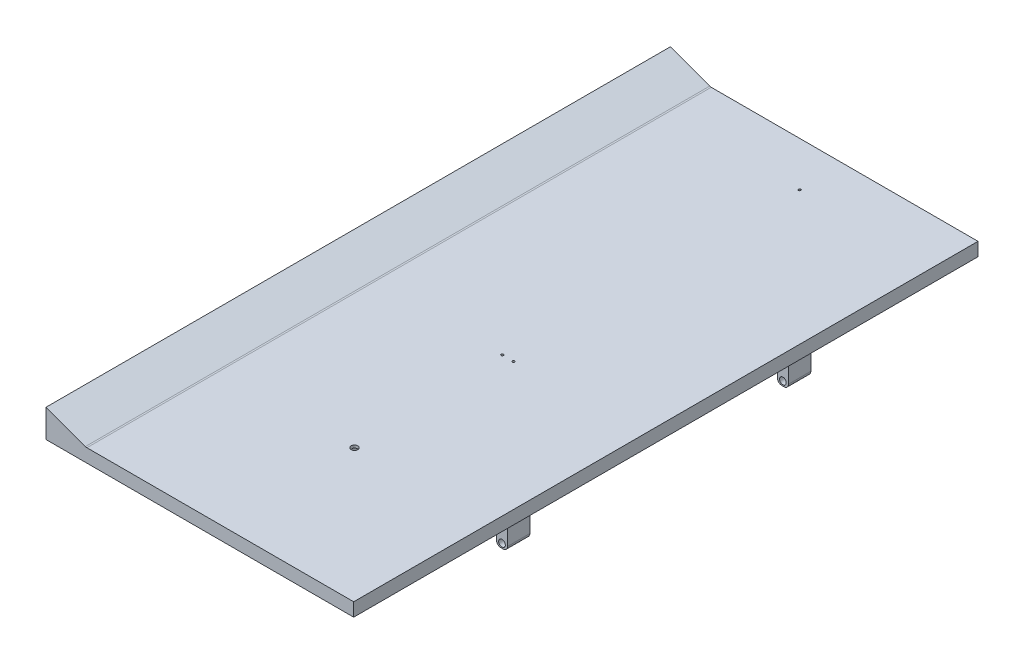
SolidWorks part; units mm, degrees
ref_plane "Front Plane" through (0, 0, 0) normal (0, 0, 1) x (1, 0, 0)
ref_plane "Top Plane" through (0, 0, 0) normal (0, 1, 0) x (1, 0, 0)
ref_plane "Right Plane" through (0, 0, 0) normal (1, 0, 0) x (0, 0, -1)
sketch "Sketch1" plane through (0, 0, 0) normal (0, 0, 1) x (1, 0, 0)
  line L0 (0, 0) -> (-598.2367, 0)
  line L1 (-601.6569, 0.6031) -> (-690, 32.7573)
  line L6 (-656.4457, -30) -> (-26.4461, -30)
  line L7 (0, -20.0005) -> (0, 0)
  line L8 (-26.4461, -30) -> (0, -30)
  line L11 (-656.4457, -30) -> (-690, -30)
  line L12 (0, -20.0005) -> (0, -30)
  line L13 (-690, -30) -> (-690, 32.7573)
  arc A2 (-598.2367, 0) -> (-601.6569, 0.6031) centre (-598.2367, 10) cw
  point P9 (-690, -30)
  point P14 (-600, 0)
  dimension "D1" = 30
  dimension "D2" = 690
  dimension "D3" = 600
  dimension "D5" = 160
extrude "Boss-Extrude1" add sketch "Sketch1" along normal blind 1040 and the other way blind 360
sketch "Sketch2" plane through (0, 0, 0) normal (0, 0, 1) x (1, 0, 0)
  line L0 (-690, 32.7573) -> (-690, -286.128) construction
  line L1 (0, -223.3332) -> (0, 223.3332) construction
  line L3 (-690, -30) -> (0, -30) construction
  line L4 (-677.5, -80) -> (-352.5, -80) construction
  line L5 (-677.5, -72.5) -> (-352.5, -72.5)
  line L6 (-677.5, -87.5) -> (-352.5, -87.5)
  line L7 (-690, -30) -> (-690, -80)
  line L8 (-680, -90) -> (-350, -90)
  line L9 (-340, -80) -> (-340, -30)
  line L10 (-690, -30) -> (0, -30) construction
  line L11 (-340, -30) -> (-690, -30)
  line L12 (-15, -30) -> (-15, -80)
  line L13 (-25, -90) -> (-30, -90)
  line L14 (-40, -80) -> (-40, -30)
  line L15 (-40, -30) -> (-15, -30)
  circle A0 centre (-27.5, -80) radius 7.5
  arc A1 (-677.5, -72.5) -> (-677.5, -87.5) centre (-677.5, -80) ccw
  arc A2 (-352.5, -87.5) -> (-352.5, -72.5) centre (-352.5, -80) ccw
  arc A3 (-690, -80) -> (-680, -90) centre (-680, -80) ccw
  arc A4 (-350, -90) -> (-340, -80) centre (-350, -80) ccw
  arc A5 (-15, -80) -> (-25, -90) centre (-25, -80) cw
  arc A6 (-30, -90) -> (-40, -80) centre (-30, -80) cw
  point P7 (0, 0)
  point P14 (-515, -80)
  point P29 (-690, -90)
  point P32 (-340, -90)
  point P40 (-15, -90)
  point P43 (-40, -90)
  dimension "D1" = 27.5
  dimension "D2" = 50
  dimension "D5" = 325
  dimension "D4" = 7.5
  dimension "D6" = 15
  dimension "D9" = 10
  dimension "D10" = 10
  dimension "D13" = 10
  dimension "D14" = 12.5
  dimension "D15" = 12.5
  dimension "D3" = 325
  dimension "D7" = 60
  dimension "D8" = 350
  dimension "D11" = 60
  dimension "D12" = 25
extrude "Boss-Extrude2" add sketch "Sketch2" along normal blind 680
sketch "Sketch4" plane through (0, 0, 0) normal (1, 0, 0) x (0, 0, -1)
  line L0 (-50, -90) -> (-50, -80)
  line L1 (-680, -90) -> (0, -90) construction
  line L2 (-680, -80) -> (0, -80) construction
  line L3 (-50, -80) -> (-630, -80)
  line L4 (-630, -80) -> (-630, -90)
  line L5 (-630, -90) -> (-50, -90)
  line L7 (-680, -80) -> (-680, -30) construction
  dimension "D1" = 580
  dimension "D2" = 50
extrude "Cut-Extrude1" cut sketch "Sketch4" against normal through all
sketch "Sketch5" plane through (-690, 0, 0) normal (-1, 0, 0) x (0, 0, 1)
  line L0 (630, -80) -> (630, -30)
  line L1 (-360, -30) -> (1040, -30) construction
  line L2 (50, -80) -> (50, -30)
  line L3 (50, -30) -> (630, -30)
  line L4 (630, -80) -> (50, -80)
extrude "Cut-Extrude2" cut sketch "Sketch5" against normal through all both and the other way through all
sketch "Sketch6" plane through (0, 0, 0) normal (0, 1, 0) x (1, 0, 0)
  line L0 (0, 360) -> (-690, 360) construction
  line L1 (-298.2367, 60) -> (-298.2367, -740) construction
  line L2 (0, -1040) -> (-598.2367, -1040) construction
  line L3 (122.7597, -740) -> (-719.2332, -740) construction
  line L4 (-598.2367, 360) -> (-598.2367, -1040) construction
  circle A0 centre (-298.2367, -740) radius 7.5
  point P11 (-298.2367, -740)
  dimension "D2" = 15
  dimension "D1" = 300
  dimension "D3" = 300
extrude "Cut-Extrude3" cut sketch "Sketch6" along normal through all both and the other way through all
sketch "Sketch8" plane through (0, -30, 0) normal (0, -1, 0) x (1, 0, 0)
  line L1 (-310.7367, 756) -> (-285.7367, 756)
  line L2 (-310.7367, 756) -> (-310.7367, 724)
  line L3 (-310.7367, 724) -> (-285.7367, 724)
  line L4 (-285.7367, 756) -> (-285.7367, 724)
  line L5 (-310.7367, 756) -> (-285.7367, 724) construction
  line L6 (-310.7367, 724) -> (-285.7367, 756) construction
  point P0 (-298.2367, 740)
  dimension "D1" = 32
  dimension "D2" = 25
extrude "Boss-Extrude4" add sketch "Sketch8" along normal blind 37.5
sketch "Sketch9" plane through (0, 0, 756) normal (0, 0, 1) x (1, 0, 0)
  line L0 (-306.2387, -30) -> (-306.2387, -62.5)
  line L1 (-285.7367, -30) -> (-310.7367, -30) construction
  line L2 (-306.2387, -62.5) -> (-290.2367, -62.5)
  line L3 (-290.2367, -62.5) -> (-290.2367, -30)
  line L4 (-290.2367, -30) -> (-306.2387, -30)
  line L5 (-285.7367, -67.5) -> (-285.7367, -30) construction
  dimension "D1" = 16.002
  dimension "D2" = 4.5
  dimension "D3" = 32.5
extrude "Cut-Extrude4" cut sketch "Sketch9" against normal blind 66.8
sketch "Sketch11" plane through (0, -30, 0) normal (0, -1, 0) x (1, 0, 0)
  line L0 (-306.2387, 772) -> (-290.2367, 772)
  line L1 (-290.2367, 772) -> (-290.2367, 708)
  line L2 (-290.2367, 708) -> (-306.2387, 708)
  line L3 (-306.2387, 708) -> (-306.2387, 772)
  line L4 (-333.9483, 740) -> (-262.5252, 740) construction
  circle A0 centre (-298.2367, 740) radius 7.5 construction
  point P12 (-298.2367, 740)
  dimension "D3" = 32
  dimension "D5" = 8
  dimension "D1" = 64
  dimension "D2" = 32
  dimension "D4" = 16.002
extrude "Cut-Extrude5" cut sketch "Sketch11" against normal blind 24
ref_plane "Plane1" through (-300, 0, 0) normal (1, 0, 0) x (0, 0, -1)
sketch "Sketch13" plane through (0, 0, 0) normal (0, 1, 0) x (1, 0, 0)
  line L0 (-300, 360) -> (-300, -1878.1794) construction
  line L1 (-300, -67.5165) -> (-300, 67.5165) construction
  line L2 (0, 360) -> (-598.2367, 360) construction
  line L3 (-312.7, -394.05) -> (-287.3, -394.05) construction
  line L4 (-510.7387, -440) -> (-89.2613, -440) construction
  line L5 (0, -1040) -> (-598.2367, -1040) construction
  circle A0 centre (-300, 260) radius 2.5908
  circle A1 centre (-287.3, -394.05) radius 2.5908
  circle A2 centre (-312.7, -394.05) radius 2.5908
  point P15 (-300, -440)
  dimension "D1" = 5.1816
  dimension "D2" = 5.1816
  dimension "D4" = 12.7
  dimension "D7" = 5.1816
  dimension "D8" = 700
  dimension "D3" = 25.4
  dimension "D5" = 600
  dimension "D6" = 654.05
extrude "Cut-Extrude6" cut sketch "Sketch13" against normal blind 20
